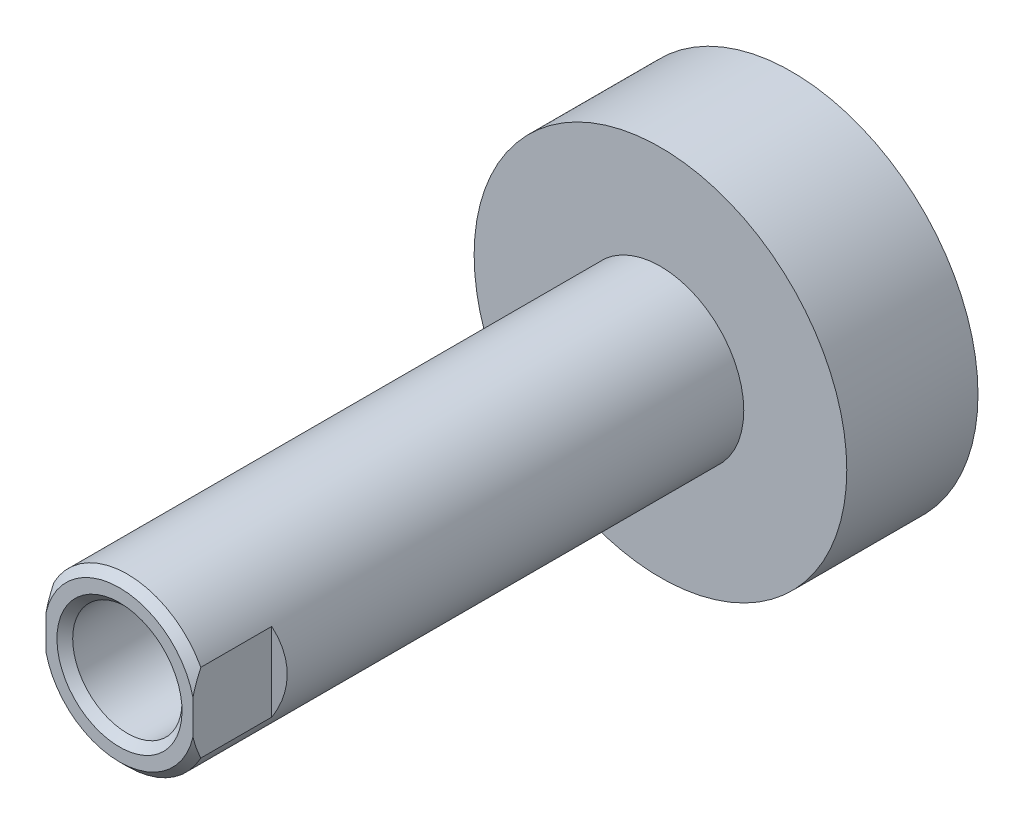
SolidWorks part; units mm, degrees
ref_plane "Front" through (0, 0, 0) normal (0, 0, 1) x (1, 0, 0)
ref_plane "Top" through (0, 0, 0) normal (0, 1, 0) x (1, 0, 0)
ref_plane "Right" through (0, 0, 0) normal (1, 0, 0) x (0, 0, -1)
sketch "Sketch1" plane through (0, 0, 0) normal (0, 0, 1) x (1, 0, 0)
  circle A0 centre (0, 0) radius 7.1
  dimension "D1" = 14.2
extrude "Piston" add sketch "Sketch1" along normal blind 5
sketch "Sketch2" plane through (0, 0, 0) normal (0, 0, -1) x (-1, 0, 0)
  circle A0 centre (0, 0) radius 3.175
  dimension "D1" = 6.35
extrude "Rod" add sketch "Sketch2" against normal up to surface (25.614 mm away)
sketch "Sketch8" plane through (0, 0, 25.614) normal (0, 0, 1) x (1, 0, 0)
  point P0 (0, 0)
hole_wizard "056 #8-32 Internal Thread" positions "3DSketch2" profile "Sketch9" tap size "#8-32" standard "Ansi Inch"
sketch3d "3DSketch2"
  point P0 (0, 0, 25.614)
sketch "Sketch9" plane through (0, 0, 25.614) normal (1, 0, 0) x (0, -1, 0)
  line L0 (0, 0) -> (0, 15.1152)
  line L1 (0, 15.1152) -> (1.7272, 14.0774)
  line L2 (1.7272, 14.0774) -> (1.7272, 11.684)
  line L3 (1.7272, 11.684) -> (2.0828, 11.684)
  line L4 (2.0828, 11.684) -> (2.0828, 0)
  line L5 (2.0828, 0) -> (0, 0)
  line L10 (0, 15.1152) -> (-1.7272, 14.0774) construction
  line L11 (0, -6.35) -> (0, 107.95) construction
  dimension "Tap Drill Dia." = 3.4544
  dimension "Tap Drill Depth" = 14.0774
  dimension "Thread Major Dia." = 4.1656
  dimension "Thread Depth" = 11.684
  dimension "Drill Angle" = 118
hole_wizard "075 #10-32 Internal Thread" [suppressed] positions "3DSketch3" profile "Sketch12" tap size "#10-32" standard "Ansi Inch"
sketch3d "3DSketch3"
  point P0 (0, 0, 50)
sketch "Sketch12" plane through (0, 0, 50) normal (1, 0, 0) x (0, -1, 0)
  line L0 (0, 0) -> (0, 15.2908)
  line L1 (0, 15.2908) -> (2.0193, 14.0774)
  line L2 (2.0193, 14.0774) -> (2.0193, 11.7)
  line L3 (2.0193, 11.7) -> (2.413, 11.7)
  line L4 (2.413, 11.7) -> (2.413, 0)
  line L5 (2.413, 0) -> (0, 0)
  line L10 (0, 15.2908) -> (-2.0193, 14.0774) construction
  line L11 (0, -6.35) -> (0, 107.95) construction
  dimension "Tap Drill Dia." = 4.0386
  dimension "Tap Drill Depth" = 14.0774
  dimension "Thread Major Dia." = 4.826
  dimension "Thread Depth" = 11.684
  dimension "Drill Angle" = 118
hole_wizard "106 5/16-24 Internal Thread" [suppressed] positions "3DSketch4" profile "Sketch13" tap size "5/16-24" standard "Ansi Inch"
sketch3d "3DSketch4"
  point P0 (0, 0, 50)
sketch "Sketch13" plane through (0, 0, 50) normal (1, 0, 0) x (0, -1, 0)
  line L0 (0, 0) -> (0, 18.4532)
  line L1 (0, 18.4532) -> (3.4544, 16.3775)
  line L2 (3.4544, 16.3775) -> (3.4544, 13.2)
  line L3 (3.4544, 13.2) -> (3.9687, 13.2)
  line L4 (3.9687, 13.2) -> (3.9687, 0)
  line L5 (3.9687, 0) -> (0, 0)
  line L10 (0, 18.4532) -> (-3.4544, 16.3775) construction
  line L11 (0, -6.35) -> (0, 107.95) construction
  dimension "Tap Drill Dia." = 6.9088
  dimension "Tap Drill Depth" = 20.4
  dimension "Thread Major Dia." = 7.9375
  dimension "Thread Depth" = 17.78
  dimension "Drill Angle" = 118
hole_wizard "150 3/8-24 Internal Thread" [suppressed] positions "3DSketch5" profile "Sketch14" tap size "3/8-24" standard "Ansi Inch"
sketch3d "3DSketch5"
  point P0 (0, 0, 50)
sketch "Sketch14" plane through (0, 0, 50) normal (1, 0, 0) x (0, -1, 0)
  line L0 (0, 0) -> (0, 18.411)
  line L1 (0, 18.411) -> (4.2164, 15.8775)
  line L2 (4.2164, 15.8775) -> (4.2164, 12.7)
  line L3 (4.2164, 12.7) -> (4.7625, 12.7)
  line L4 (4.7625, 12.7) -> (4.7625, 0)
  line L5 (4.7625, 0) -> (0, 0)
  line L10 (0, 18.411) -> (-4.2164, 15.8775) construction
  line L11 (0, -6.35) -> (0, 107.95) construction
  dimension "Tap Drill Dia." = 8.4328
  dimension "Tap Drill Depth" = 20.4
  dimension "Thread Major Dia." = 9.525
  dimension "Thread Depth" = 17.78
  dimension "Drill Angle" = 118
hole_wizard "200-250 1/2-20 Internal Thread" [suppressed] positions "3DSketch6" profile "Sketch15" tap size "1/2-20" standard "Ansi Inch"
sketch3d "3DSketch6"
  point P0 (0, 0, 122.515)
sketch "Sketch15" plane through (0, 0, 122.515) normal (1, 0, 0) x (0, -1, 0)
  line L0 (0, 0) -> (0, 23.8576)
  line L1 (0, 23.8576) -> (5.7544, 20.4)
  line L2 (5.7544, 20.4) -> (5.7544, 17.78)
  line L3 (5.7544, 17.78) -> (6.35, 17.78)
  line L4 (6.35, 17.78) -> (6.35, 0)
  line L5 (6.35, 0) -> (0, 0)
  line L10 (0, 23.8576) -> (-5.7544, 20.4) construction
  line L11 (0, -6.35) -> (0, 107.95) construction
  dimension "Tap Drill Dia." = 11.5087
  dimension "Tap Drill Depth" = 20.4
  dimension "Thread Major Dia." = 12.7
  dimension "Thread Depth" = 17.78
  dimension "Drill Angle" = 118
chamfer "Rod End Chamfer" distance 0.3 angle 45 2 edges at (0, 3.175, 25.614) (0, -2.0828, 25.614)
sketch "Sketch11" plane through (0, 0, 0) normal (0, 1, 0) x (1, 0, 0)
  line L0 (0, -25.614) -> (0, -54.2319) construction
  line L1 (-2.8, -25.614) -> (-2.8, -22.614)
  line L2 (2.8, -25.614) -> (2.8, -22.614)
  line L3 (-2.8, -22.614) -> (-7.8, -19.7272)
  line L4 (2.8, -22.614) -> (7.8, -19.7272)
  line L5 (-7.8, -19.7272) -> (-7.8, -25.614)
  line L6 (7.8, -19.7272) -> (7.8, -25.614)
  line L7 (-7.8, -25.614) -> (-2.8, -25.614)
  line L8 (7.8, -25.614) -> (2.8, -25.614)
  line L9 (-3.175, -25.614) -> (3.175, -25.614) construction
  dimension "D1" = 60
  dimension "D2" = 5
  dimension "D3" = 3
  dimension "D4" = 5.6
extrude "Wrench Flats" cut sketch "Sketch11" against normal through all and the other way through all
sketch "Sketch16" plane through (0, 0, 25.614) normal (0, 0, 1) x (1, 0, 0)
  circle A0 centre (0, 0) radius 2.0828
  dimension "D1" = 4.1656
extrude "External Thread" [suppressed] add sketch "Sketch16" along normal blind 9.652
chamfer "External Rod Thread Chamfer" [suppressed] distance 0.3 angle 45
hole_wizard "300 5/8-18 Internal Thread" [suppressed] positions "3DSketch7" profile "Sketch17" tap size "5/8-18" standard "Ansi Inch"
sketch3d "3DSketch7"
  arc A0 (7.95, 3.0778, 122.515) -> (-7.95, 3.0778, 122.515) centre (0, 0, 122.515) ccw construction
  point P6 (0, 0, 122.515)
  point P15 (0, 0, 131.04)
sketch "Sketch17" plane through (0, 0, 122.515) normal (1, 0, 0) x (0, -1, 0)
  line L0 (0, 0) -> (0, 19.8164)
  line L1 (0, 19.8164) -> (7.3419, 15.405)
  line L2 (7.3419, 15.405) -> (7.3419, 11.176)
  line L3 (7.3419, 11.176) -> (7.9375, 11.176)
  line L4 (7.9375, 11.176) -> (7.9375, 0)
  line L5 (7.9375, 0) -> (0, 0)
  line L10 (0, 19.8164) -> (-7.3419, 15.405) construction
  line L11 (0, -6.35) -> (0, 107.95) construction
  dimension "Tap Drill Dia." = 14.6837
  dimension "Tap Drill Depth" = 15.405
  dimension "Thread Major Dia." = 15.875
  dimension "Thread Depth" = 11.176
  dimension "Drill Angle" = 118
hole_wizard "400 3/4-16 Internal Thread" [suppressed] positions "3DSketch8" profile "Sketch18" tap size "3/4-16" standard "Ansi Inch"
sketch3d "3DSketch8"
  arc A0 (11.176, 3.4622, 122.515) -> (-11.176, 3.4622, 122.515) centre (0, 0, 122.515) ccw construction
  point P0 (0, 0, 122.515)
  point P9 (0, 0, 134.215)
sketch "Sketch18" plane through (0, 0, 122.515) normal (1, 0, 0) x (0, -1, 0)
  line L0 (0, 0) -> (0, 21.7563)
  line L1 (0, 21.7563) -> (8.7312, 16.51)
  line L2 (8.7312, 16.51) -> (8.7312, 16.448)
  line L3 (8.7312, 16.448) -> (9.525, 16.448)
  line L4 (9.525, 16.448) -> (9.525, 0)
  line L5 (9.525, 0) -> (0, 0)
  line L10 (0, 21.7563) -> (-8.7313, 16.51) construction
  line L11 (0, -6.35) -> (0, 107.95) construction
  dimension "Tap Drill Dia." = 17.4625
  dimension "Tap Drill Depth" = 16.51
  dimension "Thread Major Dia." = 19.05
  dimension "Thread Depth" = 16.448
  dimension "Drill Angle" = 118
